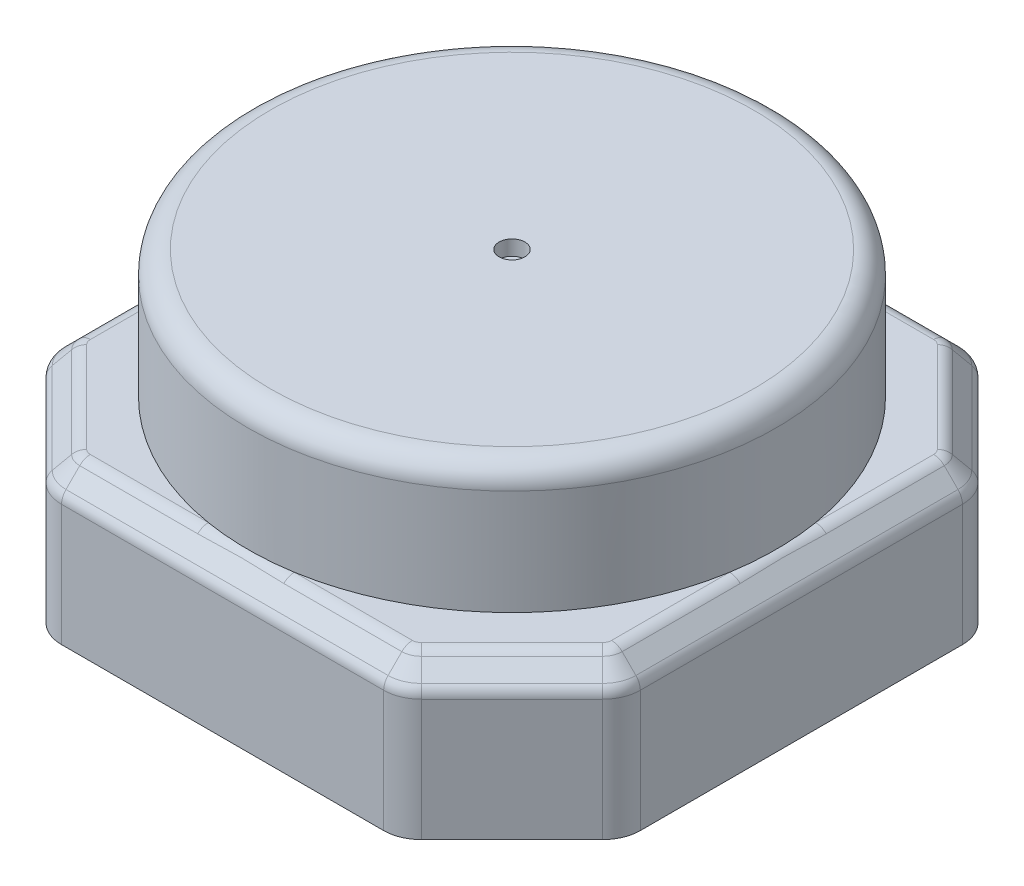
SolidWorks part; units mm, degrees
material "ABS PC"
ref_plane "Front Plane" through (0, 0, 0) normal (0, 0, 1) x (1, 0, 0)
ref_plane "Top Plane" through (0, 0, 0) normal (0, 1, 0) x (1, 0, 0)
ref_plane "Right Plane" through (0, 0, 0) normal (1, 0, 0) x (0, 0, -1)
sketch "Sketch1" plane through (0, 0, 0) normal (0, 1, 0) x (1, 0, 0)
  line L0 (0, 38.5) -> (0, -65.6059) construction
  line L1 (-38.5, 38.5) -> (38.5, 38.5)
  line L2 (-38.5, 38.5) -> (-38.5, -38.5)
  line L3 (-38.5, -38.5) -> (38.5, -38.5)
  line L4 (38.5, 38.5) -> (38.5, -38.5)
  line L5 (-38.5, 0) -> (38.5, 0) construction
  point P9 (0, 47.8551)
  point P10 (38.5, 0)
  point P11 (-38.5, 0)
  dimension "D1" = 77
extrude "Boss-Extrude2" add sketch "Sketch1" along normal blind 20
chamfer "Chamfer1" distance 15 angle 45 4 edges at (-38.5, 10, -38.5) (38.5, 10, -38.5) (-38.5, 10, 38.5) (38.5, 10, 38.5)
fillet "Fillet1" radius 5 8 edges at (23.5, 10, -38.5) (38.5, 10, -23.5) (38.5, 10, 23.5) (23.5, 10, 38.5) (-23.5, 10, -38.5) (-38.5, 10, -23.5) (-38.5, 10, 23.5) (-23.5, 10, 38.5)
chamfer "Chamfer2" distance 3 angle 45 16 edges at (-23.3423, 20, -38.1194) (-31, 20, -31) (0, 20, -38.5) (-38.1194, 20, -23.3423) (23.3423, 20, -38.1194) (-38.5, 20, 0) (31, 20, -31) (-38.1194, 20, 23.3423) (38.1194, 20, -23.3423) (-31, 20, 31) (38.5, 20, 0) (-23.3423, 20, 38.1194) (38.1194, 20, 23.3423) (0, 20, 38.5) (23.3423, 20, 38.1194) (31, 20, 31)
fillet "Fillet2" radius 2 16 edges at (23.3423, 17, 38.1194) (31, 17, 31) (38.1194, 17, 23.3423) (38.5, 17, 0) (38.1194, 17, -23.3423) (31, 17, -31) (23.3423, 17, -38.1194) (0, 17, -38.5) (-23.3423, 17, -38.1194) (-31, 17, -31) (-38.1194, 17, -23.3423) (-38.5, 17, 0) (-38.1194, 17, 23.3423) (-31, 17, 31) (-23.3423, 17, 38.1194) (0, 17, 38.5)
sketch "Sketch2" plane through (0, 20, 0) normal (0, 1, 0) x (1, 0, 0)
  line L0 (0, 35.5) -> (0, -35.5) construction
  line L1 (21.4289, 35.5) -> (-21.4289, 35.5) construction
  line L2 (-21.4289, -35.5) -> (21.4289, -35.5) construction
  line L3 (0, 0) -> (-35.5, 0) construction
  line L4 (-35.5, 21.4289) -> (-35.5, -21.4289) construction
  circle A0 centre (0, 0) radius 35.1409
extrude "Boss-Extrude3" add sketch "Sketch2" along normal blind 17
fillet "Fillet3" radius 3 1 edges at (0, 37, 35.1409)
sketch "Sketch3" plane through (0, 37, 0) normal (0, 1, 0) x (1, 0, 0)
  circle A0 centre (0, 0) radius 1.7166
extrude "Cut-Extrude1" cut sketch "Sketch3" against normal blind 2
fillet "Fillet4" radius 2 16 edges at (-35.3478, 20, 22.1943) (-35.5, 20, 0) (-35.3478, 20, -22.1943) (-28.8787, 20, -28.8787) (-22.1943, 20, -35.3478) (0, 20, -35.5) (22.1943, 20, -35.3478) (28.8787, 20, -28.8787) (35.3478, 20, -22.1943) (35.5, 20, 0) (35.3478, 20, 22.1943) (28.8787, 20, 28.8787) (22.1943, 20, 35.3478) (0, 20, 35.5) (-22.1943, 20, 35.3478) (-28.8787, 20, 28.8787)
